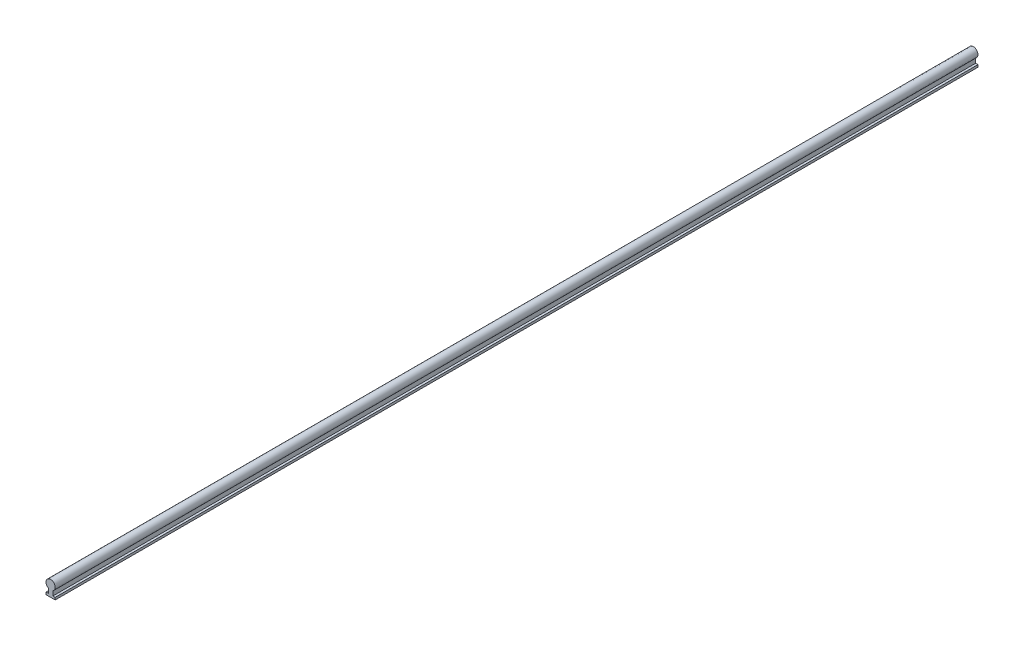
SolidWorks part; units mm, degrees
material "1023 Carbon Steel Sheet (SS)"
ref_plane "Front Plane" through (0, 0, 0) normal (0, 0, 1) x (1, 0, 0)
ref_plane "Top Plane" through (0, 0, 0) normal (0, 1, 0) x (1, 0, 0)
ref_plane "Right Plane" through (0, 0, 0) normal (1, 0, 0) x (0, 0, -1)
sketch "Sketch2" plane through (0, 0, 0) normal (0, 0, 1) x (1, 0, 0)
  line L0 (-5, -5) -> (5, -5)
  line L1 (-2.5, -2.5) -> (-2.5, 2.5)
  line L2 (2.5, -2.5) -> (2.5, 2.5)
  line L5 (0, -2.5) -> (0, 10) construction
  line L7 (-5, -2.5) -> (-2.5, -2.5)
  line L8 (5, -5) -> (5, -2.5)
  line L9 (-5, -5) -> (-5, -2.5)
  line L12 (-10, -5) -> (10, -5) construction
  line L13 (-10, -2.5) -> (10, -2.5) construction
  line L15 (-5, -5) -> (-5, 20) construction
  line L17 (5, -5) -> (5, 20) construction
  line L18 (0, -5) -> (0, 20) construction
  line L19 (2.5, -2.5) -> (5, -2.5)
  arc A0 (2.5, 2.5) -> (-2.5, 2.5) centre (0, 6.8301) ccw
  point P0 (0, 0)
  point P1 (0, 0)
  point P23 (0, 0)
  dimension "D7" = 5
  dimension "D1" = 5
  dimension "D2" = 5
  dimension "D8" = 2.5
  dimension "D3" = 2.5
  dimension "D4" = 2.5
  dimension "D5" = 5
  dimension "D6" = 5
extrude "Boss-Extrude1" add sketch "Sketch2" along normal blind 1000
